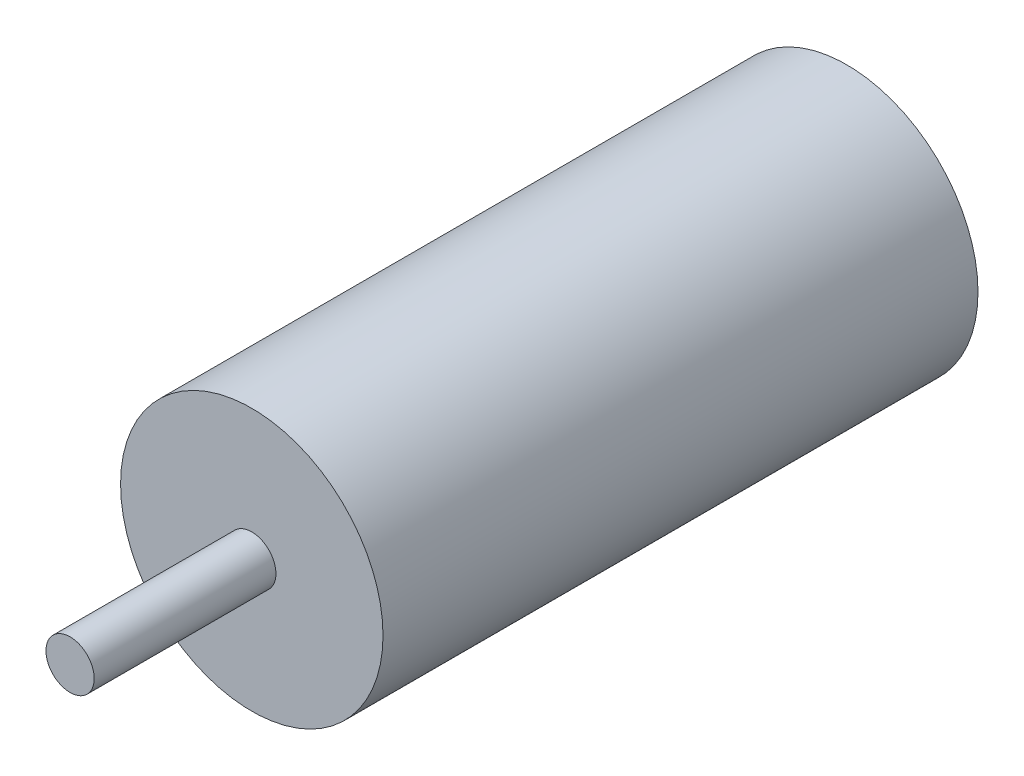
SolidWorks part; units mm, degrees
ref_plane "Front Plane" through (0, 0, 0) normal (0, 0, 1) x (1, 0, 0)
ref_plane "Top Plane" through (0, 0, 0) normal (0, 1, 0) x (1, 0, 0)
ref_plane "Right Plane" through (0, 0, 0) normal (1, 0, 0) x (0, 0, -1)
sketch "Sketch1" plane through (0, 0, 0) normal (0, 0, 1) x (1, 0, 0)
  circle A0 centre (0, 0) radius 11.049
  dimension "D1" = 22.098
extrude "Boss-Extrude1" add sketch "Sketch1" along normal blind 50.1
sketch "Sketch2" plane through (0, 0, 50.1) normal (0, 0, 1) x (1, 0, 0)
  circle A0 centre (0, 0) radius 2.032
  dimension "D1" = 4.064
extrude "Boss-Extrude2" add sketch "Sketch2" along normal blind 15.3001
